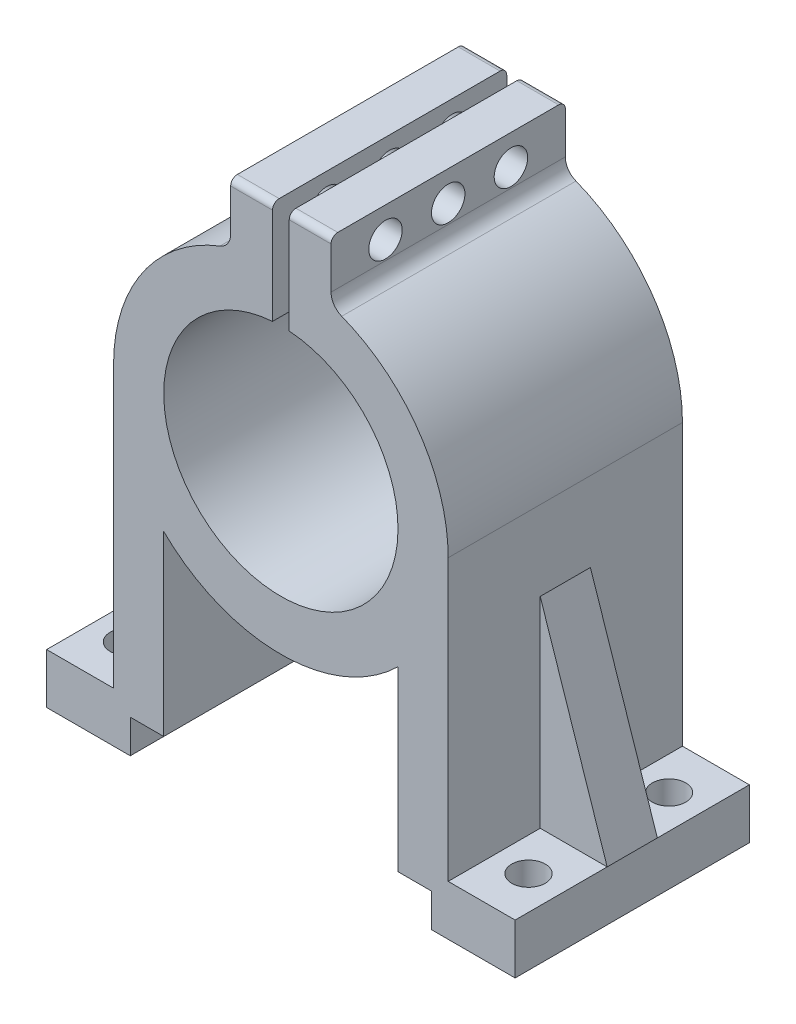
SolidWorks part; units mm, degrees
ref_plane "Front Plane" through (0, 0, 0) normal (0, 0, 1) x (1, 0, 0)
ref_plane "Top Plane" through (0, 0, 0) normal (0, 1, 0) x (1, 0, 0)
ref_plane "Right Plane" through (0, 0, 0) normal (1, 0, 0) x (0, 0, -1)
sketch "Sketch1" plane through (0, 0, 0) normal (0, 0, 1) x (1, 0, 0)
  line L0 (0, 10) -> (0, -10) construction
  line L1 (0, 10) -> (0, 7)
  line L2 (0, -7) -> (0, -10)
  line L3 (10, 0) -> (10, -16.7519)
  line L4 (10, -16.7519) -> (14, -16.7519)
  line L5 (14, -16.7519) -> (14, -19.7519)
  line L6 (14, -19.7519) -> (7, -19.7519)
  line L7 (7, -19.7519) -> (7, -7.1414)
  arc A0 (0, -7) -> (0, 7) centre (0, 0) ccw
  arc A1 (0, -10) -> (7, -7.1414) centre (0, 0) ccw
  arc A2 (10, 0) -> (0, 10) centre (0, 0) ccw
  point P8 (14, -18.2519)
  dimension "D1" = 20
  dimension "D2" = 14
  dimension "D3" = 4
  dimension "D4" = 7
  dimension "D5" = 3
extrude "Boss-Extrude1" add sketch "Sketch1" along normal mid plane 14
sketch "Sketch3" plane through (0, -16.7519, 0) normal (0, 1, 0) x (1, 0, 0)
  line L0 (14, -7) -> (14, 7) construction
  line L1 (14, -7) -> (10, -7) construction
  line L2 (14, 7) -> (10, 7) construction
  line L3 (10, 0) -> (14, 0) construction
  line L4 (10, -7) -> (10, 7) construction
  circle A0 centre (12, -4.2) radius 1
  circle A1 centre (12, 4.2) radius 1
  dimension "D1" = 2
  dimension "D2" = 2
  dimension "D3" = 2.8
  dimension "D4" = 2.8
  dimension "D5" = 2
  dimension "D6" = 7
extrude "Cut-Extrude1" cut sketch "Sketch3" against normal blind 10
sketch "Sketch2" plane through (0, 0, 0) normal (0, 0, 1) x (1, 0, 0)
  line L2 (14, -16.7519) -> (10, -4.7519)
  dimension "D1" = 12
rib "Rib1" sketch "Sketch2" sketch "Sketch2" thickness 3 extrusion direction parallel to sketch draft on no parameters "D1"=3
sketch "Sketch4" plane through (0, 0, 0) normal (0, 0, 1) x (1, 0, 0)
  line L2 (0, 10) -> (0, 13.1394)
  line L3 (0, 13.1394) -> (3, 13.1394)
  line L4 (3, 13.1394) -> (3, 9.5394)
  arc A0 (10, 0) -> (0, 10) centre (0, 0) ccw construction
  arc A1 (3, 9.5394) -> (0, 10) centre (0, 0) ccw
  dimension "D2" = 3.6
  dimension "D1" = 3
extrude "Boss-Extrude2" add sketch "Sketch4" along normal mid plane 14
sketch "Sketch5" plane through (3, 0, 0) normal (1, 0, 0) x (0, 0, -1)
  line L0 (-7, 11.3394) -> (7, 11.3394) construction
  line L1 (-7, 9.5394) -> (-7, 13.1394) construction
  line L2 (7, 9.5394) -> (7, 13.1394) construction
  circle A0 centre (-3.75, 11.3394) radius 1
  circle A1 centre (0, 11.3394) radius 1
  circle A2 centre (3.75, 11.3394) radius 1
  point P12 (0, 0)
  point P13 (0, 11.3394)
  point P14 (0, 0)
  point P15 (0, 0)
  point P16 (0, 11.3394)
  point P17 (0, 11.3394)
  point P18 (0, 0)
  point P19 (0, 0)
  dimension "D1" = 2
  dimension "D2" = 7
  dimension "D3" = 3.25
  dimension "D4" = 3.25
extrude "Cut-Extrude2" cut sketch "Sketch5" against normal blind 14
fillet "Fillet1" radius 1 1 edges at (3, 9.5394, 0)
fillet "Fillet2" radius 0.4 2 edges at (1.5, 13.1394, -7) (1.5, 13.1394, 7)
sketch "Sketch6" plane through (0, 0, 7) normal (0, 0, 1) x (1, 0, 0)
  line L0 (7, -17.7519) -> (9, -17.7519)
  line L1 (7, -17.7519) -> (7, -21.9737)
  line L2 (9, -17.7519) -> (9, -21.9737)
  line L3 (7, -21.9737) -> (9, -21.9737)
  line L4 (7, -7.1414) -> (7, -19.7519) construction
  line L5 (7, -19.7519) -> (14, -19.7519) construction
  dimension "D1" = 2
  dimension "D2" = 2
extrude "Cut-Extrude3" cut sketch "Sketch6" against normal through all
mirror "Mirror1" about plane through (0, 0, 0) normal (1, 0, 0) of bodies 105
sketch "Sketch7" plane through (0, 0, 7) normal (0, 0, 1) x (1, 0, 0)
  line L0 (0, 12.7394) -> (0, 7) construction
  line L1 (3, 12.7394) -> (-3, 12.7394) construction
  line L3 (-0.5, 18.9296) -> (0.5, 18.9296)
  line L4 (-0.5, 18.9296) -> (-0.5, 0.8098)
  line L5 (-0.5, 0.8098) -> (0.5, 0.8098)
  line L6 (0.5, 18.9296) -> (0.5, 0.8098)
  line L7 (-0.5, 18.9296) -> (0.5, 0.8098) construction
  line L8 (-0.5, 0.8098) -> (0.5, 18.9296) construction
  circle A0 centre (0, 0) radius 7 construction
  point P7 (0, 9.8697)
  dimension "D1" = 1
extrude "Cut-Extrude4" cut sketch "Sketch7" against normal through all
